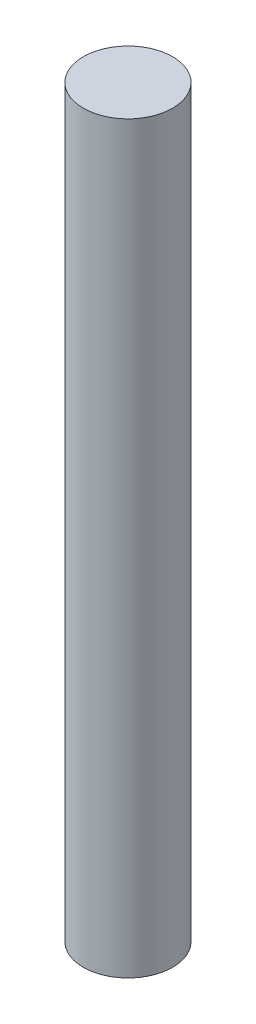
SolidWorks part; units mm, degrees
material "AISI 4340 钢，正火"
ref_plane "前视基准面" through (0, 0, 0) normal (0, 0, 1) x (1, 0, 0)
ref_plane "上视基准面" through (0, 0, 0) normal (0, 1, 0) x (1, 0, 0)
ref_plane "右视基准面" through (0, 0, 0) normal (1, 0, 0) x (0, 0, -1)
other "Configuration Table"
sketch "草图1" plane through (0, 0, 0) normal (0, 1, 0) x (1, 0, 0)
  circle A0 centre (0, 0) radius 1.5
extrude "凸台-拉伸1" add sketch "草图1" along normal blind 25
